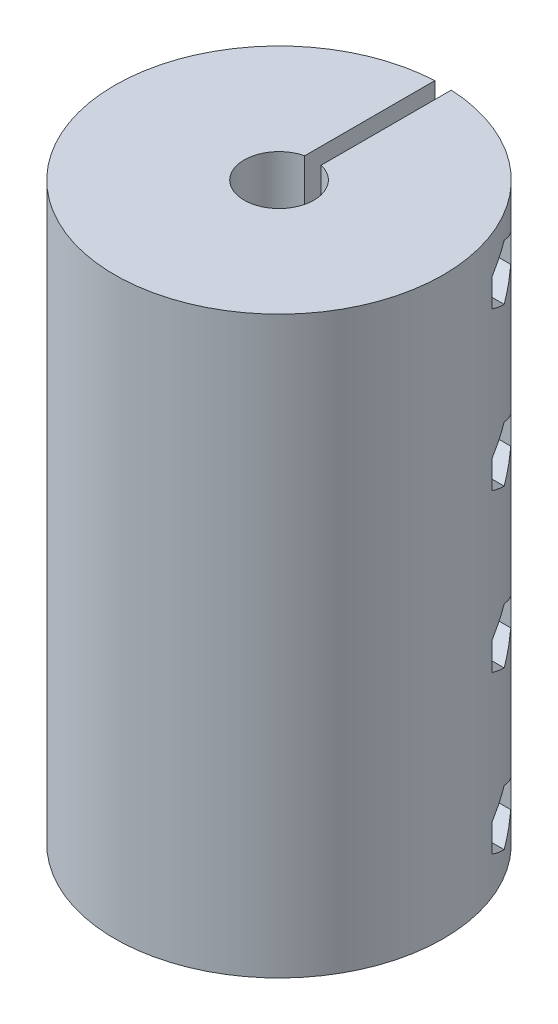
SolidWorks part; units mm, degrees
ref_plane "Front Plane" through (0, 0, 0) normal (0, 0, 1) x (1, 0, 0)
ref_plane "Top Plane" through (0, 0, 0) normal (0, 1, 0) x (1, 0, 0)
ref_plane "Right Plane" through (0, 0, 0) normal (1, 0, 0) x (0, 0, -1)
sketch "Sketch1" plane through (0, 0, 0) normal (0, 1, 0) x (1, 0, 0)
  circle A0 centre (0, 0) radius 20
  circle A1 centre (0, 0) radius 4.25
  dimension "D1" = 40
  dimension "D2" = 8.5
extrude "Boss-Extrude1" add sketch "Sketch1" along normal mid plane 70
sketch "Sketch2" plane through (0, 0, 0) normal (0, 1, 0) x (1, 0, 0)
  line L1 (-1, 0) -> (1, 0)
  line L2 (-1, 0) -> (-1, 25)
  line L3 (-1, 25) -> (1, 25)
  line L4 (1, 0) -> (1, 25)
  point P4 (0, 0)
  dimension "D1" = 2
  dimension "D2" = 0
  dimension "D3" = 25
extrude "Cut-Extrude1" cut sketch "Sketch2" against normal mid plane 70
ref_plane "Plane1" through (20, 0, 0) normal (1, 0, 0) x (0, 0, -1)
ref_plane "Plane2" through (-20, 0, 0) normal (1, 0, 0) x (0, 0, -1)
sketch "Sketch4" plane through (20, 0, 0) normal (1, 0, 0) x (0, 0, -1)
  line L0 (19.975, 35) -> (-20, 35) construction
  line L1 (-20, -35) -> (19.975, -35) construction
  circle A0 centre (10.2317, 28.75) radius 1.75
  circle A4 centre (10.2317, 9.5833) radius 1.75
  circle A5 centre (10.2317, -9.5833) radius 1.75
  circle A6 centre (10.2317, -28.75) radius 1.75
  dimension "D1" = 3.5
  dimension "D3" = 6.25
  dimension "D4" = 6.25
  dimension "D2" = 4
extrude "Cut-Extrude2" cut sketch "Sketch4" against normal blind 30
sketch "Sketch5" plane through (20, 0, 0) normal (1, 0, 0) x (0, 0, -1)
  line L1 (10.2317, 32.1275) -> (7.3067, 30.4387)
  line L2 (7.3067, 30.4387) -> (7.3067, 27.0613)
  line L3 (7.3067, 27.0613) -> (10.2317, 25.3725)
  line L4 (10.2317, 25.3725) -> (13.1567, 27.0613)
  line L5 (13.1567, 27.0613) -> (13.1567, 30.4387)
  line L6 (13.1567, 30.4387) -> (10.2317, 32.1275)
  line L24 (10.2317, 6.2058) -> (13.1567, 7.8946)
  line L25 (7.3067, 7.8946) -> (10.2317, 6.2058)
  line L26 (7.3067, 11.2721) -> (7.3067, 7.8946)
  line L27 (10.2317, 12.9608) -> (7.3067, 11.2721)
  line L28 (13.1567, 11.2721) -> (10.2317, 12.9608)
  line L29 (13.1567, 7.8946) -> (13.1567, 11.2721)
  line L30 (10.2317, -12.9608) -> (13.1567, -11.2721)
  line L31 (7.3067, -11.2721) -> (10.2317, -12.9608)
  line L32 (7.3067, -7.8946) -> (7.3067, -11.2721)
  line L33 (10.2317, -6.2058) -> (7.3067, -7.8946)
  line L34 (13.1567, -7.8946) -> (10.2317, -6.2058)
  line L35 (13.1567, -11.2721) -> (13.1567, -7.8946)
  line L36 (10.2317, -32.1275) -> (13.1567, -30.4387)
  line L37 (7.3067, -30.4387) -> (10.2317, -32.1275)
  line L38 (7.3067, -27.0613) -> (7.3067, -30.4387)
  line L39 (10.2317, -25.3725) -> (7.3067, -27.0613)
  line L40 (13.1567, -27.0613) -> (10.2317, -25.3725)
  line L41 (13.1567, -30.4387) -> (13.1567, -27.0613)
  circle A0 centre (10.2317, 28.75) radius 2.925 construction
  point P1 (13.1567, 28.75)
  dimension "D1" = 5.85
  dimension "D2" = 4
extrude "Cut-Extrude3" cut sketch "Sketch5" against normal blind 11
sketch "Sketch6" plane through (-20, 0, 0) normal (1, 0, 0) x (0, 0, -1)
  line L0 (-20, -35) -> (19.975, -35) construction
  circle A0 centre (10.2317, 28.75) radius 3
  circle A1 centre (10.2317, 9.5833) radius 3
  circle A2 centre (10.2317, -9.5833) radius 3
  circle A3 centre (10.2317, -28.75) radius 3
  dimension "D1" = 6
  dimension "D3" = 6.25
  dimension "D2" = 4
extrude "Cut-Extrude4" cut sketch "Sketch6" along normal blind 11
